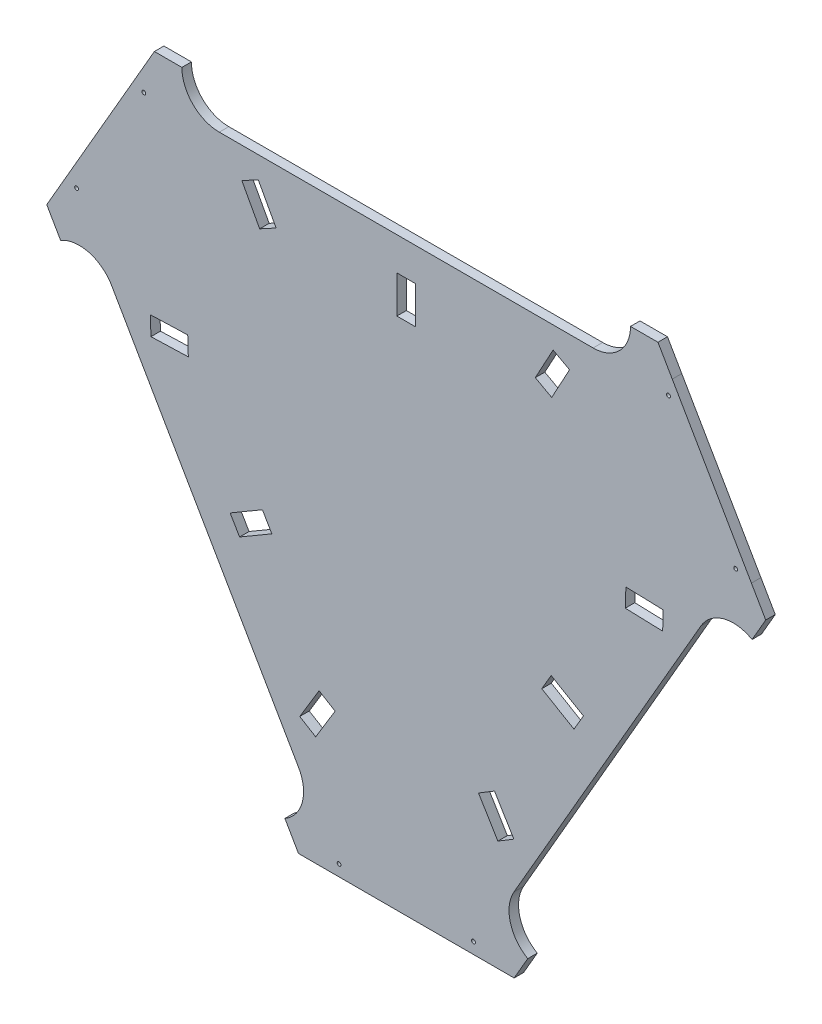
SolidWorks part; units mm, degrees
ref_plane "Plan de face" through (0, 0, 0) normal (0, 0, 1) x (1, 0, 0)
ref_plane "Plan de dessus" through (0, 0, 0) normal (0, 1, 0) x (1, 0, 0)
ref_plane "Plan de droite" through (0, 0, 0) normal (1, 0, 0) x (0, 0, -1)
sketch "Model" plane through (0, 0, 0) normal (0, 0, 1) x (1, 0, 0)
  line L729 (682.695, -1946.8551) -> (879.1515, -2287.128)
  line L730 (864.7723, -2340.792) -> (879.0808, -2365.5749)
  line L731 (879.0808, -2365.5749) -> (909.4074, -2365.5749)
  line L732 (909.4074, -2365.5749) -> (1075.3934, -2365.5749)
  line L733 (1075.3934, -2365.5749) -> (1105.72, -2365.5749)
  line L734 (1105.72, -2365.5749) -> (1120.0285, -2340.792)
  line L735 (1105.6493, -2287.128) -> (1302.1058, -1946.8551)
  line L736 (1355.7698, -1932.4759) -> (1370.1781, -1907.52)
  line L737 (1370.1781, -1907.52) -> (1355.1147, -1881.4294)
  line L738 (1355.1147, -1881.4294) -> (1271.9291, -1737.348)
  line L739 (1271.9291, -1737.348) -> (1271.9291, -1737.3477)
  line L740 (1271.9291, -1737.3477) -> (1256.8866, -1711.2929)
  line L741 (1256.8866, -1711.2929) -> (1228.0351, -1711.2929)
  line L742 (1188.7438, -1750.5842) -> (795.8306, -1750.5842)
  line L743 (756.5393, -1711.2929) -> (727.6174, -1711.2929)
  line L744 (727.6174, -1711.2929) -> (614.4744, -1907.2629)
  line L745 (614.4744, -1907.2629) -> (629.031, -1932.4759)
  line L1029 (1223.1756, -1950.9126) -> (1262.447, -1952.1643)
  line L1030 (1262.447, -1952.1643) -> (1261.8212, -1971.8)
  line L1031 (1261.8212, -1971.8) -> (1222.5496, -1970.5482)
  line L1032 (1222.5496, -1970.5482) -> (1223.1756, -1950.9126)
  line L1033 (1168.6774, -2107.5762) -> (1134.7563, -2087.748)
  line L1034 (1134.7563, -2087.748) -> (1144.6705, -2070.7874)
  line L1035 (1144.6705, -2070.7874) -> (1178.5917, -2090.6157)
  line L1036 (1178.5917, -2090.6157) -> (1168.6774, -2107.5762)
  line L1037 (1146.6881, -1773.4759) -> (1163.9559, -1782.8448)
  line L1038 (1163.9559, -1782.8448) -> (1145.2184, -1817.3803)
  line L1039 (1145.2184, -1817.3803) -> (1127.9506, -1808.0115)
  line L1040 (1127.9506, -1808.0115) -> (1146.6881, -1773.4759)
  line L1041 (1085.081, -2205.7214) -> (1105.4405, -2239.3264)
  line L1042 (1105.4405, -2239.3264) -> (1088.638, -2249.5062)
  line L1043 (1088.638, -2249.5062) -> (1068.2784, -2215.9011)
  line L1044 (1068.2784, -2215.9011) -> (1085.081, -2205.7214)
  line L1045 (982.4641, -1785.3698) -> (1002.1099, -1785.3698)
  line L1046 (1002.1099, -1785.3698) -> (1002.1099, -1824.6611)
  line L1047 (1002.1099, -1824.6611) -> (982.4641, -1824.6611)
  line L1048 (982.4641, -1824.6611) -> (982.4641, -1785.3698)
  line L1049 (900.7401, -2206.5877) -> (917.5426, -2216.7675)
  line L1050 (917.5426, -2216.7675) -> (897.1831, -2250.3725)
  line L1051 (897.1831, -2250.3725) -> (880.3806, -2240.1928)
  line L1052 (880.3806, -2240.1928) -> (900.7401, -2206.5877)
  line L1053 (836.8088, -1773.4759) -> (855.5463, -1808.0115)
  line L1054 (855.5463, -1808.0115) -> (838.2785, -1817.3803)
  line L1055 (838.2785, -1817.3803) -> (819.541, -1782.8448)
  line L1056 (819.541, -1782.8448) -> (836.8088, -1773.4759)
  line L1057 (841.1509, -2071.6538) -> (851.0652, -2088.6143)
  line L1058 (851.0652, -2088.6143) -> (817.144, -2108.4425)
  line L1059 (817.144, -2108.4425) -> (807.2298, -2091.482)
  line L1060 (807.2298, -2091.482) -> (841.1509, -2071.6538)
  line L1061 (762.6458, -1951.7789) -> (763.2715, -1971.4146)
  line L1062 (763.2715, -1971.4146) -> (724.0002, -1972.6663)
  line L1063 (724.0002, -1972.6663) -> (723.3745, -1953.0307)
  line L1064 (723.3745, -1953.0307) -> (762.6458, -1951.7789)
  circle A1 centre (716.4917, -1754.2051) radius 2
  circle A3 centre (645.8522, -1876.5564) radius 2
  circle A5 centre (921.7609, -2353.747) radius 2
  circle A7 centre (1063.0399, -2353.747) radius 2
  circle A10 centre (1338.6022, -1876.5564) radius 2
  circle A12 centre (1267.9626, -1754.2051) radius 2
  spline S751 degree 3 poles (879.1515, -2287.128) (889.9998, -2305.9176) (883.562, -2329.9436) (864.7723, -2340.792) knots 1 1 1 1 2 2 2 2
  spline S752 degree 3 poles (1120.0285, -2340.792) (1101.2388, -2329.9436) (1094.801, -2305.9176) (1105.6493, -2287.128) knots 7 7 7 7 8 8 8 8
  spline S753 degree 3 poles (1302.1058, -1946.8551) (1312.954, -1928.0654) (1336.9802, -1921.6278) (1355.7698, -1932.4759) knots 9 9 9 9 10 10 10 10
  spline S754 degree 3 poles (1228.0351, -1711.2929) (1228.0351, -1732.9929) (1210.4438, -1750.5842) (1188.7438, -1750.5842) knots 17 17 17 17 18 18 18 18
  spline S755 degree 3 poles (795.8306, -1750.5842) (774.1306, -1750.5842) (756.5393, -1732.9929) (756.5393, -1711.2929) knots 19 19 19 19 20 20 20 20
  spline S756 degree 3 poles (629.031, -1932.4759) (647.8206, -1921.6276) (671.8468, -1928.0654) (682.695, -1946.8551) knots 23 23 23 23 24 24 24 24
  dimension "D1" = 4
  dimension "D2" = 4
  dimension "D3" = 4
  dimension "D4" = 4
  dimension "D5" = 4
  dimension "D6" = 4
extrude "Boss.-Extru.1" add sketch "Model" along normal blind 10
